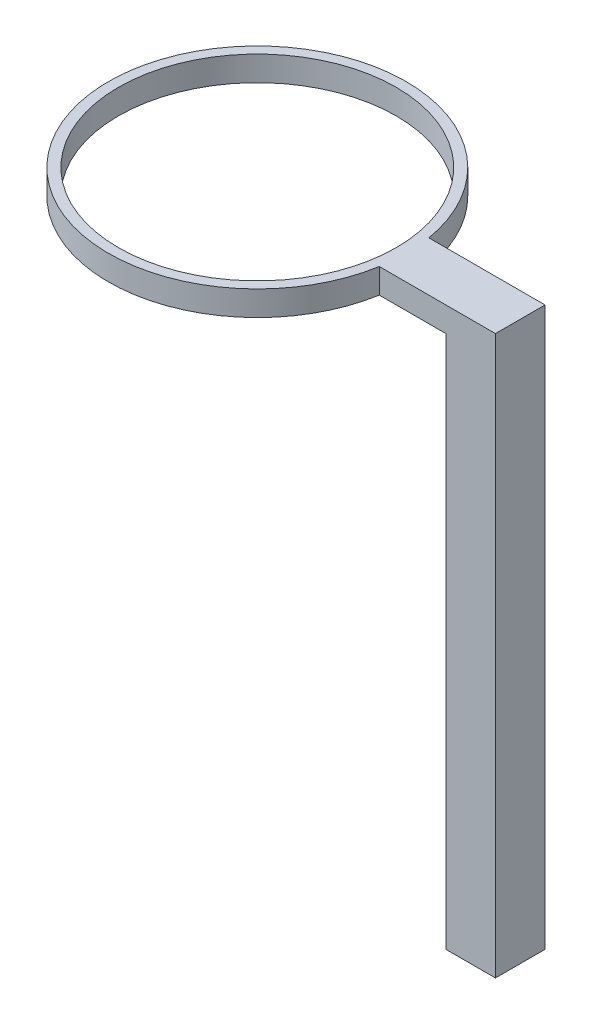
SolidWorks part; units mm, degrees
ref_plane "Plan de face" through (0, 0, 0) normal (0, 0, 1) x (1, 0, 0)
ref_plane "Plan de dessus" through (0, 0, 0) normal (0, 1, 0) x (1, 0, 0)
ref_plane "Plan de droite" through (0, 0, 0) normal (1, 0, 0) x (0, 0, -1)
sketch "Esquisse3" plane through (0, 0, 0) normal (0, 0, 1) x (1, 0, 0)
  line L0 (0, 0) -> (0, 70)
  line L1 (0, 70) -> (10, 70)
  line L2 (10, 70) -> (10, 0)
  line L3 (10, 0) -> (0, 0)
  dimension "D1" = 70
  dimension "D2" = 10
extrude "Boss.-Extru.1" add sketch "Esquisse3" along normal mid plane 10
ref_plane "Plan2" through (0, 110, 0) normal (0, 1, 0) x (1, 0, 0)
sketch "Esquisse8" plane through (0, 110, 0) normal (0, 1, 0) x (1, 0, 0)
  line L0 (10, -5) -> (10, 5)
  line L1 (10, 5) -> (-12, 5)
  line L2 (-12, 5) -> (-12, -5)
  line L3 (-12, -5) -> (10, -5)
  circle A0 centre (-43, 0) radius 30
  circle A1 centre (-43, 0) radius 28
  dimension "D1" = 60
  dimension "D2" = 56
  dimension "D3" = 22
  dimension "D4" = 31
  dimension "D5" = 5
extrude "Boss.-Extru.4" add sketch "Esquisse8" along normal mid plane 5 separate body
sketch "Esquisse9" plane through (0, 70, 0) normal (0, 1, 0) x (1, 0, 0)
  line L4 (10, 5) -> (0, 5)
  line L5 (0, 5) -> (0, -5)
  line L6 (0, -5) -> (10, -5)
  line L7 (10, -5) -> (10, 5)
  line L8 (10, 5) -> (0, 5)
  line L9 (0, 5) -> (0, -5)
  line L10 (0, -5) -> (10, -5)
  line L11 (10, -5) -> (10, 5)
  dimension "D1" = 0
extrude "Boss.-Extru.5" add sketch "Esquisse9" along normal up to next
sketch "Esquisse10" plane through (-12, 0, 0) normal (-1, 0, 0) x (0, 0, 1)
  line L4 (-5, 107.5) -> (5, 107.5)
  line L5 (5, 107.5) -> (5, 112.5)
  line L6 (5, 112.5) -> (-5, 112.5)
  line L7 (-5, 112.5) -> (-5, 107.5)
  line L8 (-5, 107.5) -> (5, 107.5)
  line L9 (5, 107.5) -> (5, 112.5)
  line L10 (5, 112.5) -> (-5, 112.5)
  line L11 (-5, 112.5) -> (-5, 107.5)
  dimension "D1" = 0
extrude "Boss.-Extru.6" add sketch "Esquisse10" along normal up to next
sketch "Esquisse11" plane through (0, 0, 0) normal (-1, 0, 0) x (0, 0, 1)
  line L0 (-5, 0) -> (-5, 12) construction
  line L1 (-5, 107.5) -> (-5, 0) construction
  line L2 (-5, 12) -> (5, 12) construction
  line L3 (5, 107.5) -> (5, 0) construction
  line L4 (5, 12) -> (5, 0) construction
  line L5 (5, 0) -> (-5, 0) construction
  circle A0 centre (0, 7.5) radius 2
  dimension "D1" = 4
  dimension "D2" = 12
  dimension "D3" = 5
  dimension "D4" = 4.5
extrude "Enlèv. mat.-Extru.1" cut sketch "Esquisse11" against normal blind 6
